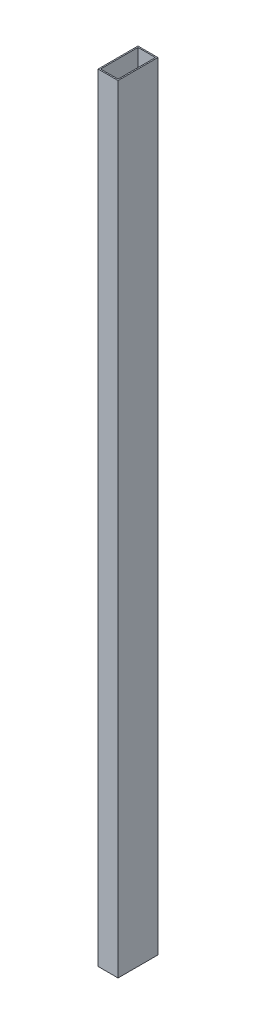
SolidWorks part; units mm, degrees
ref_plane "Front Plane" through (0, 0, 0) normal (0, 0, 1) x (1, 0, 0)
ref_plane "Top Plane" through (0, 0, 0) normal (0, 1, 0) x (1, 0, 0)
ref_plane "Right Plane" through (0, 0, 0) normal (1, 0, 0) x (0, 0, -1)
sketch "Sketch2" plane through (0, 0, 0) normal (0, 1, 0) x (1, 0, 0)
  line L1 (0, 0) -> (25.4, 0)
  line L2 (0, 0) -> (0, 50.8)
  line L3 (0, 50.8) -> (25.4, 50.8)
  line L4 (25.4, 0) -> (25.4, 50.8)
  dimension "D1" = 25.4
  dimension "D2" = 50.8
extrude "Extrude-Thin1" add sketch "Sketch2" along normal blind 990.6 thin thin type one direction reverse wall 1.524
